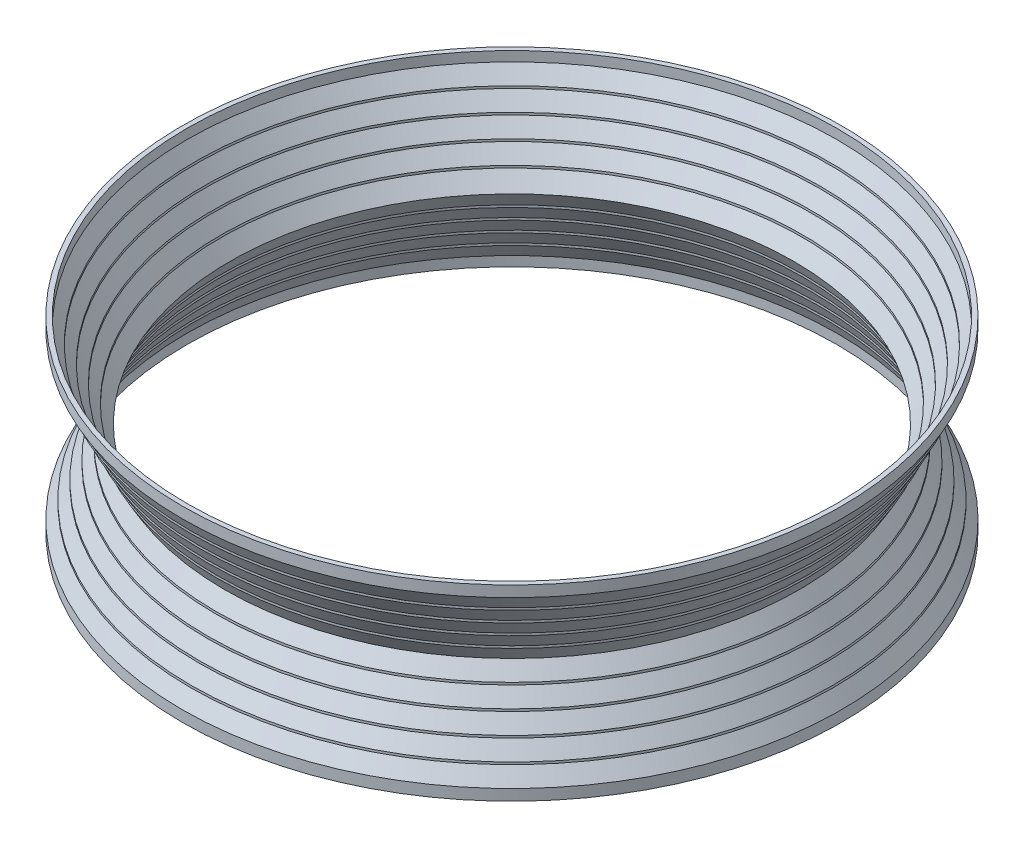
SolidWorks part; units mm, degrees
ref_plane "정면" through (0, 0, 0) normal (0, 0, 1) x (1, 0, 0)
ref_plane "윗면" through (0, 0, 0) normal (0, 1, 0) x (1, 0, 0)
ref_plane "우측면" through (0, 0, 0) normal (1, 0, 0) x (0, 0, -1)
sketch "스케치1" plane through (0, 0, 0) normal (0, 1, 0) x (1, 0, 0)
  circle A7 centre (0, 0) radius 35.8938
  dimension "D2" = 71.7876
extrude "보스-돌출1" add sketch "스케치1" along normal blind 1.2
ref_plane "평면1" through (0, 10.2, 0) normal (0, 1, 0) x (1, 0, 0)
sketch "스케치3" plane through (0, 10.2, 0) normal (0, 1, 0) x (1, 0, 0)
  circle A0 centre (0, 0) radius 27.5887
  dimension "D1" = 55.1775
sketch "스케치4" plane through (0, 0, 0) normal (1, 0, 0) x (0, 0, -1)
  line L1 (27.5887, 10.2) -> (-27.5887, 10.2) construction
  line L2 (0, 10.2) -> (0, 1.2) construction
  line L3 (35.8938, 1.2) -> (-35.8938, 1.2) construction
  line L4 (-35.8938, 1.2) -> (-34.97, 2.8)
  line L5 (-34.97, 2.8) -> (-34.97, 3.05)
  line L6 (-34.97, 3.05) -> (-34.0463, 4.65)
  line L7 (-35.8938, 1.2) -> (-30.6977, 10.2) construction
  line L8 (0, 10.2) -> (-30.6977, 10.2) construction
  line L9 (-34.0463, 4.65) -> (-34.0463, 4.9)
  line L10 (-34.0463, 4.9) -> (-33.1225, 6.5)
  line L11 (-33.1225, 6.5) -> (-33.1225, 6.75)
  line L12 (-33.1225, 6.75) -> (-32.1988, 8.35)
  line L13 (0, 10.2) -> (30.6977, 10.2) construction
  line L14 (-30.6977, 10.2) -> (0, 10.2)
  line L15 (0, 10.2) -> (0, 1.2)
  line L16 (-35.8938, 1.2) -> (0, 1.2)
  line L17 (-32.1988, 8.35) -> (-32.1988, 8.6)
  line L18 (-32.1988, 8.6) -> (-31.275, 10.2)
  line L19 (-30.6977, 10.2) -> (-31.275, 10.2)
  line L20 (-15.3488, 10.2) -> (-15.3488, 0)
  line L21 (-35.8938, 0) -> (35.8938, 0) construction
  dimension "D1" = 1.6
  dimension "D2" = 60
  dimension "D3" = 0.25
  dimension "D4" = 60
revolve "회전1" add sketch "스케치4" angle 360 about L15
mirror "대칭 복사1" of "회전1", "보스-돌출1"
shell "쉘1" thickness 0.5
